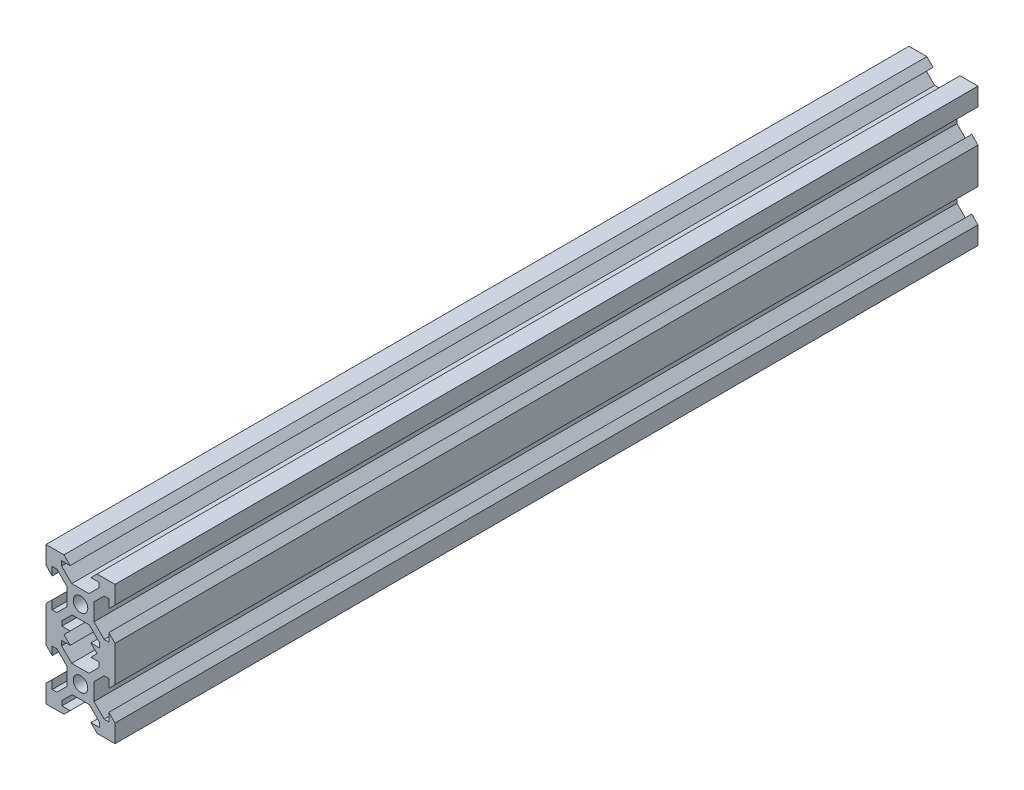
SolidWorks part; units mm, degrees
ref_plane "Alzado" through (0, 0, 0) normal (0, 0, 1) x (1, 0, 0)
ref_plane "Planta" through (0, 0, 0) normal (0, 1, 0) x (1, 0, 0)
ref_plane "Vista lateral" through (0, 0, 0) normal (1, 0, 0) x (0, 0, -1)
sketch "Croquis1" plane through (0, 0, 0) normal (0, 0, 1) x (1, 0, 0)
  line L0 (0, 20.9127) -> (0, 3.9) construction
  line L1 (-24.1207, 0) -> (-3.9, 0) construction
  line L2 (3, 8.2) -> (5.4, 8.2)
  line L3 (-10, 10) -> (-4.8, 10)
  line L4 (8.2, -3) -> (8.2, -5.4)
  line L5 (10, 10) -> (10, 4.8)
  line L6 (3.9, 2.55) -> (3.9, -2.45)
  line L7 (8.2, 5.5) -> (8.2, 3)
  line L8 (-2.55, 3.9) -> (2.45, 3.9)
  line L9 (8.2, 5.5) -> (6.85, 5.5)
  line L10 (8.2, -5.4) -> (6.85, -5.4)
  line L11 (8.2, -3) -> (10, -4.8)
  line L12 (-5.5, 8.2) -> (-3, 8.2)
  line L13 (-5.5, 8.2) -> (-5.5, 6.85)
  line L14 (10, -10) -> (10, -4.8)
  line L15 (5.4, 8.2) -> (5.4, 6.85)
  line L16 (3, 8.2) -> (4.8, 10)
  line L17 (10, 10) -> (4.8, 10)
  line L18 (8.2, 3) -> (10, 4.8)
  line L19 (6.85, 5.5) -> (3.9, 2.55)
  line L20 (6.85, -5.4) -> (3.9, -2.45)
  line L21 (20.9127, 0) -> (3.9, 0) construction
  line L22 (-3, -8.2) -> (-5.4, -8.2)
  line L23 (10, -10) -> (4.8, -10)
  line L24 (2.55, -3.9) -> (-2.45, -3.9)
  line L25 (5.5, -8.2) -> (3, -8.2)
  line L26 (5.5, -8.2) -> (5.5, -6.85)
  line L27 (-5.4, -8.2) -> (-5.4, -6.85)
  line L28 (-3, -8.2) -> (-4.8, -10)
  line L29 (-10, -10) -> (-4.8, -10)
  line L30 (3, -8.2) -> (4.8, -10)
  line L31 (5.5, -6.85) -> (2.55, -3.9)
  line L32 (-5.4, -6.85) -> (-2.45, -3.9)
  line L33 (0, -20.9127) -> (0, -3.9) construction
  line L34 (-8.2, 3) -> (-8.2, 5.4)
  line L35 (-10, -10) -> (-10, -4.8)
  line L36 (-3.9, -2.55) -> (-3.9, 2.45)
  line L37 (-8.2, -5.5) -> (-8.2, -3)
  line L38 (-8.2, -5.5) -> (-6.85, -5.5)
  line L39 (-8.2, 5.4) -> (-6.85, 5.4)
  line L40 (-3, 8.2) -> (-4.8, 10)
  line L41 (-8.2, 3) -> (-10, 4.8)
  line L42 (-5.5, 6.85) -> (-2.55, 3.9)
  line L43 (-10, 10) -> (-10, 4.8)
  line L44 (5.4, 6.85) -> (2.45, 3.9)
  line L45 (-8.2, -3) -> (-10, -4.8)
  line L46 (-6.85, -5.5) -> (-3.9, -2.55)
  line L47 (-6.85, 5.4) -> (-3.9, 2.45)
  line L48 (-20.9127, 0) -> (-3.9, 0) construction
  circle A0 centre (0, 0) radius 2.1
  point P45 (-0.05, 0.05)
  point P64 (0, 0)
  dimension "D5" = 4
  dimension "D1" = 45
  dimension "D2" = 45
  dimension "D3" = 6
  dimension "D4" = 3
  dimension "D6" = 8.2
extrude "Saliente-Extruir1" add sketch "Croquis1" along normal blind 250
sketch "Croquis2" plane through (0, 0, 250) normal (0, 0, 1) x (1, 0, 0)
  line L0 (0, 0) -> (0, 10.107) construction
pattern_linear "MatrizL1" count 2 spacing 20 along (0, -1, 0) of "Saliente-Extruir1"
